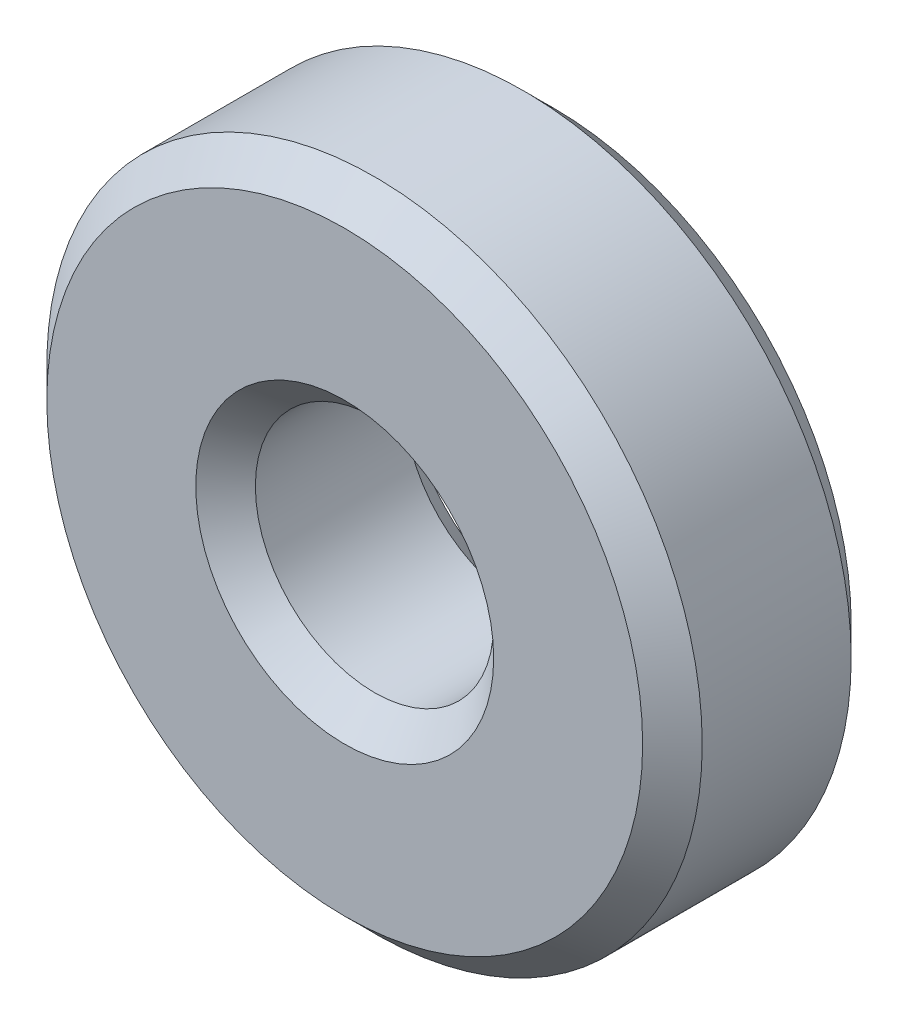
SolidWorks part; units mm, degrees
ref_plane "Přední rovina" through (0, 0, 0) normal (0, 0, 1) x (1, 0, 0)
ref_plane "Horní rovina" through (0, 0, 0) normal (0, 1, 0) x (1, 0, 0)
ref_plane "Pravá rovina" through (0, 0, 0) normal (1, 0, 0) x (0, 0, -1)
sketch "Skica1" plane through (0, 0, 0) normal (0, 0, 1) x (1, 0, 0)
  circle A0 centre (0, 0) radius 11
  circle A1 centre (0, 0) radius 4
  dimension "D1" = 8
  dimension "D2" = 22
extrude "Přidat vysunutím1" add sketch "Skica1" along normal blind 7
chamfer "Zkosení1" distance 1 angle 45 4 edges at (4, 0, 0) (4, 0, 7) (11, 0, 0) (11, 0, 7)
